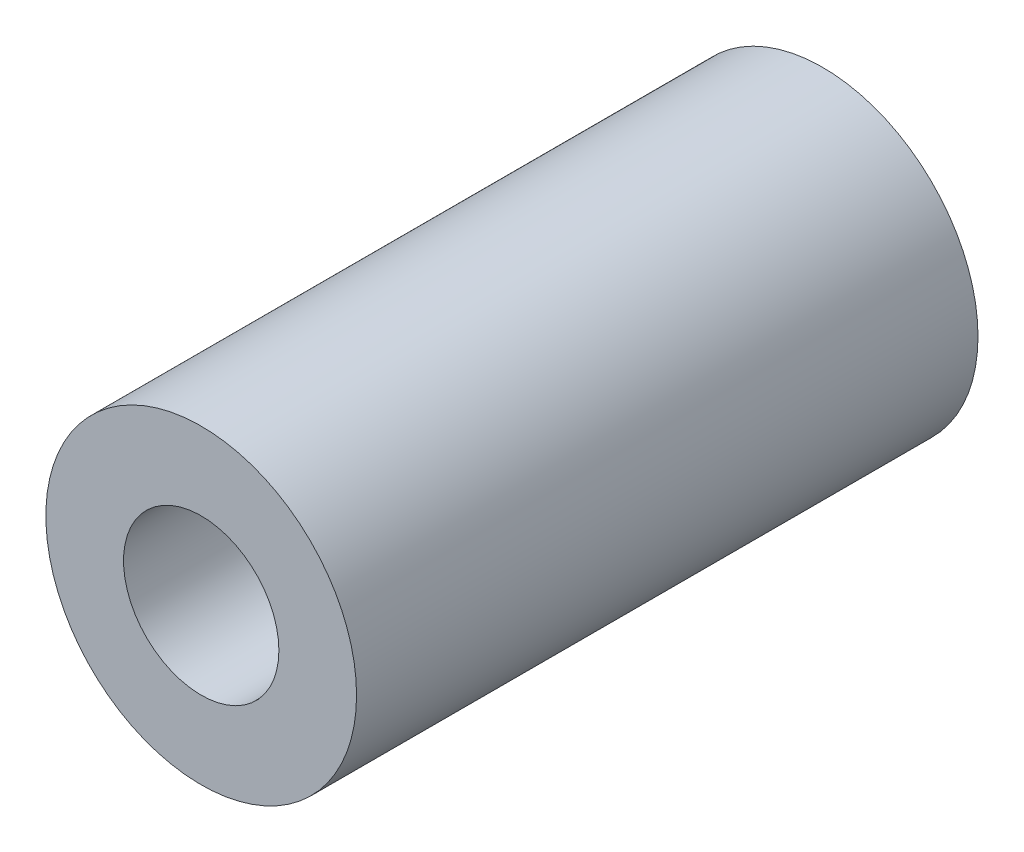
SolidWorks part; units mm, degrees
ref_plane "Front Plane" through (0, 0, 0) normal (1, 0, 0) x (0, 1, 0)
ref_plane "Top Plane" through (0, 0, 0) normal (0, 0, 1) x (0, 1, 0)
ref_plane "Right Plane" through (0, 0, 0) normal (0, 1, 0) x (-1, 0, 0)
sketch "Sketch1" plane through (0, 0, 0) normal (0, 0, 1) x (0, 1, 0)
  circle A0 centre (0, 0) radius 2.54
  circle A1 centre (0, 0) radius 5.08
  dimension "D1" = 5.08
  dimension "D2" = 2.54
extrude "Boss-Extrude1" add sketch "Sketch1" along normal blind 20.32
